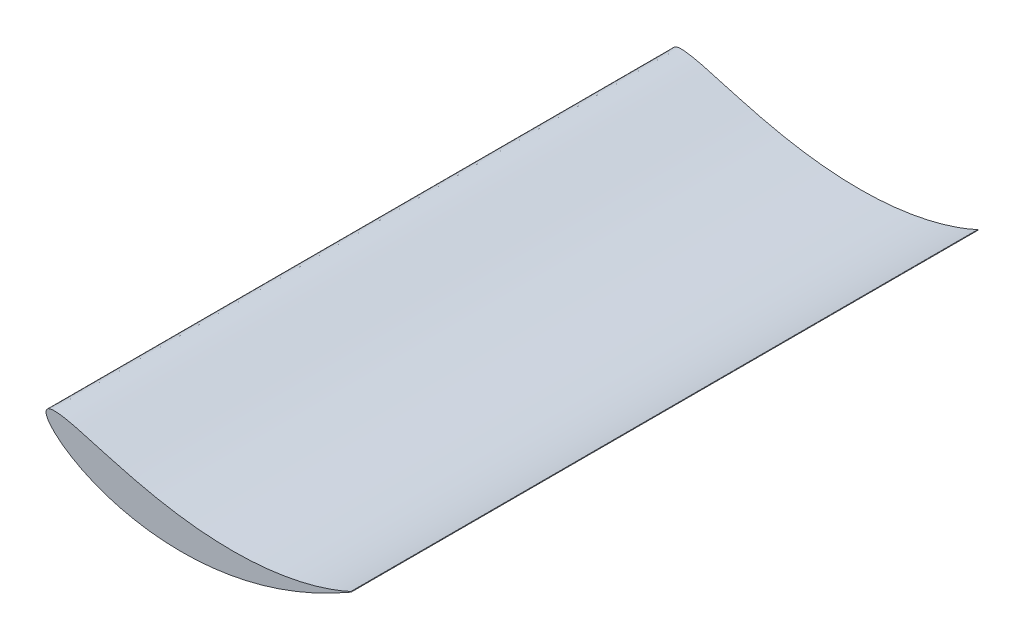
SolidWorks part; units mm, degrees
material "Thornel Mat VMA"
ref_plane "Front Plane" through (0, 0, 0) normal (0, 0, 1) x (1, 0, 0)
ref_plane "Top Plane" through (0, 0, 0) normal (0, 1, 0) x (1, 0, 0)
ref_plane "Right Plane" through (0, 0, 0) normal (1, 0, 0) x (0, 0, -1)
sketch "Sketch2" plane through (0, 0, 0) normal (0, 0, 1) x (1, 0, 0)
  line L0 (486.2971, -5.9558) -> (486.6573, -6.7323) construction
  arc A1 (486.2971, -5.9558) -> (486.6573, -6.7323) centre (486.4772, -6.3441) cw
  spline S2 degree 3 poles (486.6573, -6.7323) (486.0856, -7.0568) (482.7375, -8.9539) (475.6922, -12.9114) (465.0271, -18.734) (452.0591, -25.5368) (436.7456, -33.14) (418.9784, -41.3489) (398.7209, -49.8868) (375.9849, -58.4126) (350.8714, -66.5322) (323.5839, -73.8122) (294.4489, -79.81) (263.9237, -84.1208) (232.585, -86.4089) (201.1066, -86.4627) (170.2142, -84.2175) (140.6332, -79.7748) (113.0307, -73.3946) (87.9664, -65.4662) (65.8589, -56.4635) (46.9692, -46.8983) (31.4082, -37.2673) (19.1505, -28.0132) (10.069, -19.5081) (3.9341, -11.9907) (0.5037, -5.6317) (-0.5337, -0.1725) (1.4927, 4.1874) (5.893, 6.4543) (11.6824, 7.2978) (19.0053, 7.0772) (27.7479, 5.8828) (37.8079, 3.8475) (49.0567, 1.1004) (61.3798, -2.2174) (74.6698, -5.9658) (88.827, -10.0099) (103.7585, -14.2197) (119.3756, -18.4727) (135.5918, -22.6598) (152.3231, -26.6783) (169.4858, -30.4386) (186.9965, -33.8617) (204.7719, -36.8792) (222.7274, -39.4367) (240.7786, -41.4876) (258.8404, -42.9996) (276.8275, -43.9504) (294.6546, -44.3291) (312.2372, -44.1358) (329.491, -43.3808) (346.3332, -42.0859) (362.6821, -40.2823) (378.458, -38.0121) (393.5829, -35.3249) (407.9818, -32.281) (421.5813, -28.9487) (434.3116, -25.4059) (446.1033, -21.7341) (456.8921, -18.0262) (466.6112, -14.3787) (475.2048, -10.8903) (481.6252, -8.1002) (485.1966, -6.4664) (486.2971, -5.9558) knots 0.014458 0.014458 0.014458 0.014458 0.016355 0.025589 0.037068 0.050855 0.066985 0.085458 0.106225 0.12918 0.154149 0.180883 0.209058 0.238272 0.268058 0.297904 0.32727 0.355624 0.382465 0.407356 0.429935 0.449939 0.467202 0.481655 0.493326 0.502345 0.508967 0.513684 0.517466 0.521651 0.527066 0.533952 0.5423 0.552018 0.562982 0.575063 0.588129 0.602057 0.616727 0.632029 0.647858 0.664118 0.680718 0.697573 0.714603 0.731732 0.74889 0.766005 0.783014 0.799852 0.816455 0.832763 0.848714 0.864247 0.879299 0.893808 0.90771 0.920938 0.933424 0.945097 0.955881 0.965701 0.974472 0.982112 0.985541 0.985541 0.985541 0.985541
extrude "Boss-Extrude2" add sketch "Sketch2" along normal mid plane 1000 contours S2 A1
